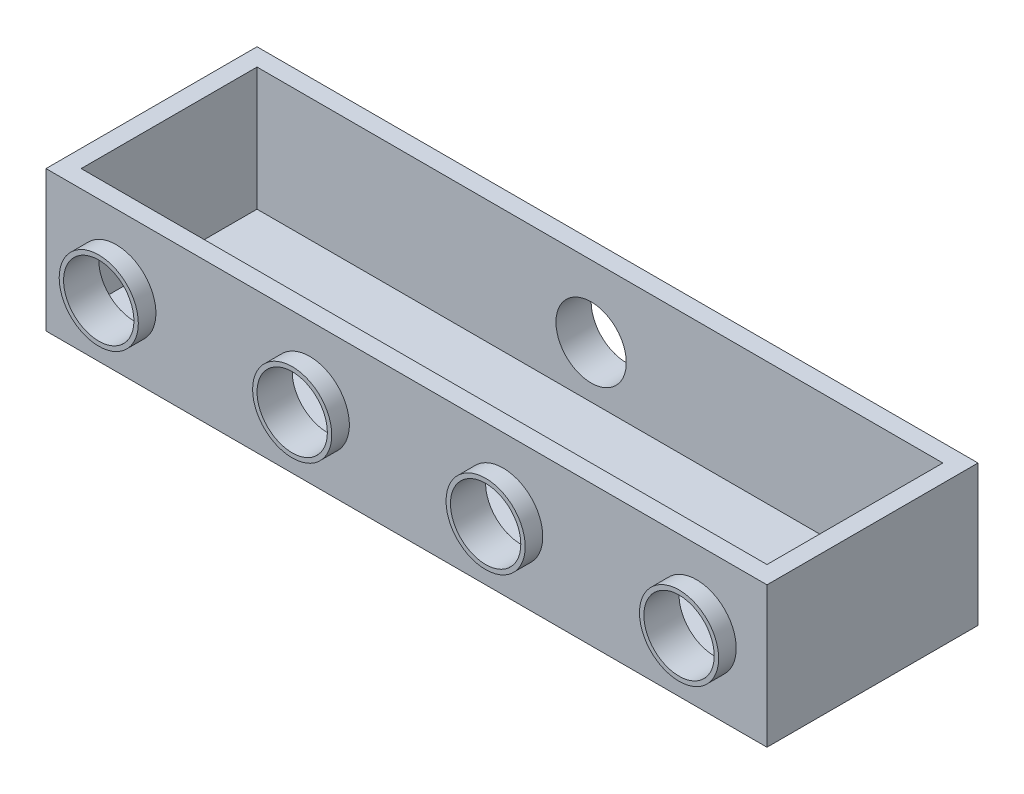
SolidWorks part; units mm, degrees
ref_plane "Front Plane" through (0, 0, 0) normal (0, 0, 1) x (1, 0, 0)
ref_plane "Top Plane" through (0, 0, 0) normal (0, 1, 0) x (1, 0, 0)
ref_plane "Right Plane" through (0, 0, 0) normal (1, 0, 0) x (0, 0, -1)
sketch "Sketch1" plane through (0, 0, 0) normal (0, 1, 0) x (1, 0, 0)
  line L1 (0, 0) -> (1041.4, 0)
  line L2 (0, 0) -> (0, 304.8)
  line L3 (0, 304.8) -> (1041.4, 304.8)
  line L4 (1041.4, 0) -> (1041.4, 304.8)
  dimension "D1" = 1041.4
  dimension "D2" = 304.8
extrude "Boss-Extrude1" add sketch "Sketch1" along normal blind 203.2
sketch "Sketch2" plane through (0, 0, 0) normal (-1, 0, 0) x (0, 0, 1)
  line L0 (0, 203.2) -> (0, 0) construction
  circle A0 centre (-76.2, 101.3147) radius 33.3293
  dimension "D1" = 76.2
sketch "Sketch3" plane through (0, 0, 0) normal (0, 0, 1) x (1, 0, 0)
  line L0 (0, 203.2) -> (1041.4, 203.2) construction
  line L1 (0, 203.2) -> (0, 0) construction
  circle A0 centre (101.6, 101.6) radius 57.15
  circle A1 centre (381, 101.6) radius 57.15
  circle A2 centre (660.4, 101.6) radius 57.15
  circle A3 centre (939.8, 101.6) radius 57.15
  dimension "D2" = 114.3
  dimension "D4" = 114.3
  dimension "D6" = 114.3
  dimension "D8" = 114.3
  dimension "D1" = 101.6
  dimension "D3" = 101.6
  dimension "D5" = 279.4
  dimension "D7" = 279.4
  dimension "D9" = 279.4
extrude "Boss-Extrude2" add sketch "Sketch3" along normal blind 25.4
sketch "Sketch4" plane through (0, 0, -304.8) normal (0, 0, -1) x (-1, 0, 0)
  line L0 (-1041.4, 203.2) -> (-1041.4, 0) construction
  circle A0 centre (-508, 100.0709) radius 57.15
  dimension "D1" = 114.3
  dimension "D2" = 533.4
extrude "Boss-Extrude3" add sketch "Sketch4" along normal blind 25.4
sketch "Sketch5" plane through (0, 203.2, 0) normal (0, 1, 0) x (1, 0, 0)
  line L0 (0, 304.8) -> (0, 0) construction
  line L1 (25.4, 25.4) -> (1016, 25.4)
  line L2 (25.4, 25.4) -> (25.4, 279.4)
  line L3 (25.4, 279.4) -> (1016, 279.4)
  line L4 (1016, 25.4) -> (1016, 279.4)
  line L5 (1041.4, 0) -> (1041.4, 304.8) construction
  line L6 (1041.4, 304.8) -> (0, 304.8) construction
  line L7 (0, 0) -> (1041.4, 0) construction
  dimension "D1" = 25.4
  dimension "D2" = 25.4
  dimension "D3" = 25.4
  dimension "D4" = 25.4
extrude "Cut-Extrude1" cut sketch "Sketch5" against normal blind 177.8
sketch "Sketch6" plane through (0, 0, 25.4) normal (0, 0, 1) x (1, 0, 0)
  circle A0 centre (101.6, 101.6) radius 50.8
  circle A1 centre (381, 101.6) radius 50.8
  circle A2 centre (660.4, 101.6) radius 50.8
  circle A3 centre (939.8, 101.6) radius 50.8
  dimension "D1" = 101.6
  dimension "D2" = 101.6
  dimension "D3" = 101.6
  dimension "D4" = 101.6
extrude "Cut-Extrude2" cut sketch "Sketch6" against normal blind 177.8
sketch "Sketch7" plane through (0, 0, -330.2) normal (0, 0, -1) x (-1, 0, 0)
  circle A0 centre (-508, 100.0709) radius 50.8
  dimension "D1" = 101.6
extrude "Cut-Extrude3" cut sketch "Sketch7" against normal blind 177.8
